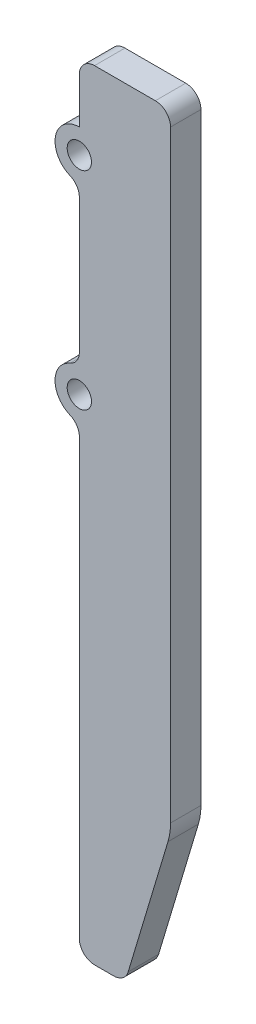
SolidWorks part; units mm, degrees
ref_plane "前基準面" through (0, 0, 0) normal (0, 0, 1) x (1, 0, 0)
ref_plane "上基準面" through (0, 0, 0) normal (0, 1, 0) x (1, 0, 0)
ref_plane "右基準面" through (0, 0, 0) normal (1, 0, 0) x (0, 0, -1)
sketch "草圖1" plane through (0, 0, 0) normal (0, 0, 1) x (1, 0, 0)
  line L0 (-17.0002, -31.5465) -> (-9.5002, -6.5465)
  line L2 (-24.5002, 44.4535) -> (-24.5002, -31.5465)
  line L3 (-24.5002, -31.5465) -> (-17.0002, -31.5465)
  line L4 (-9.5002, 96.5535) -> (-9.5002, -6.5465)
  line L5 (-24.5002, 78.5535) -> (-24.5002, 52.4535)
  line L6 (-9.5002, 96.5535) -> (-24.5002, 96.5535)
  line L7 (-24.5002, 96.5535) -> (-24.5002, 86.5535)
  arc A0 (-24.5002, 86.5535) -> (-24.5002, 78.5535) centre (-24.5002, 82.5535) ccw
  arc A1 (-24.5002, 52.4535) -> (-24.5002, 44.4535) centre (-24.5002, 48.4535) ccw
  circle A2 centre (-24.5002, 82.5535) radius 2
  circle A3 centre (-24.5002, 48.4535) radius 2
  dimension "D2" = 8
  dimension "D4" = 34.1
  dimension "D6" = 4
  dimension "D7" = 4
  dimension "D9" = 80
  dimension "D1" = 10
  dimension "D8" = 25
extrude "填料-伸長1" add sketch "草圖1" along normal blind 5
fillet "圓角1" radius 2.5 4 edges at (-24.5002, -31.5465, 2.5) (-17.0002, -31.5465, 2.5) (-9.5002, 96.5535, 2.5) (-24.5002, 96.5535, 2.5)
fillet "圓角2" radius 2.5 3 edges at (-24.5002, 52.4535, 2.5) (-24.5002, 44.4535, 2.5) (-24.5002, 78.5535, 2.5)
fillet "圓角3" radius 10 1 edges at (-9.5002, -6.5465, 2.5)
